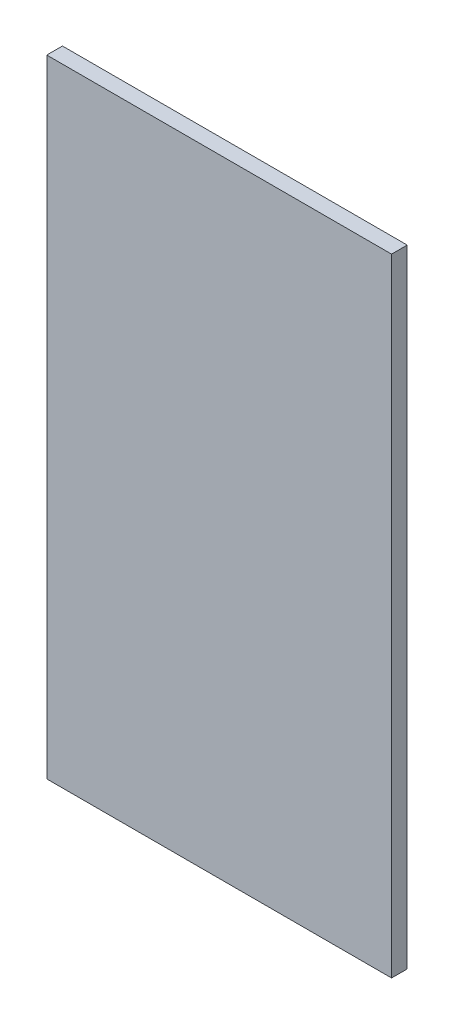
SolidWorks part; units mm, degrees
ref_plane "Alzado" through (0, 0, 0) normal (0, 0, 1) x (1, 0, 0)
ref_plane "Planta" through (0, 0, 0) normal (0, 1, 0) x (1, 0, 0)
ref_plane "Vista lateral" through (0, 0, 0) normal (1, 0, 0) x (0, 0, -1)
sketch "Croquis1" plane through (0, 0, 0) normal (0, 0, 1) x (1, 0, 0)
  line L1 (-110, -200) -> (110, -200)
  line L2 (-110, -200) -> (-110, 200)
  line L3 (-110, 200) -> (110, 200)
  line L4 (110, -200) -> (110, 200)
  line L5 (-110, -200) -> (110, 200) construction
  line L6 (-110, 200) -> (110, -200) construction
  point P0 (0, 0)
  dimension "D1" = 220
  dimension "D2" = 400
extrude "Saliente-Extruir1" add sketch "Croquis1" along normal blind 10
